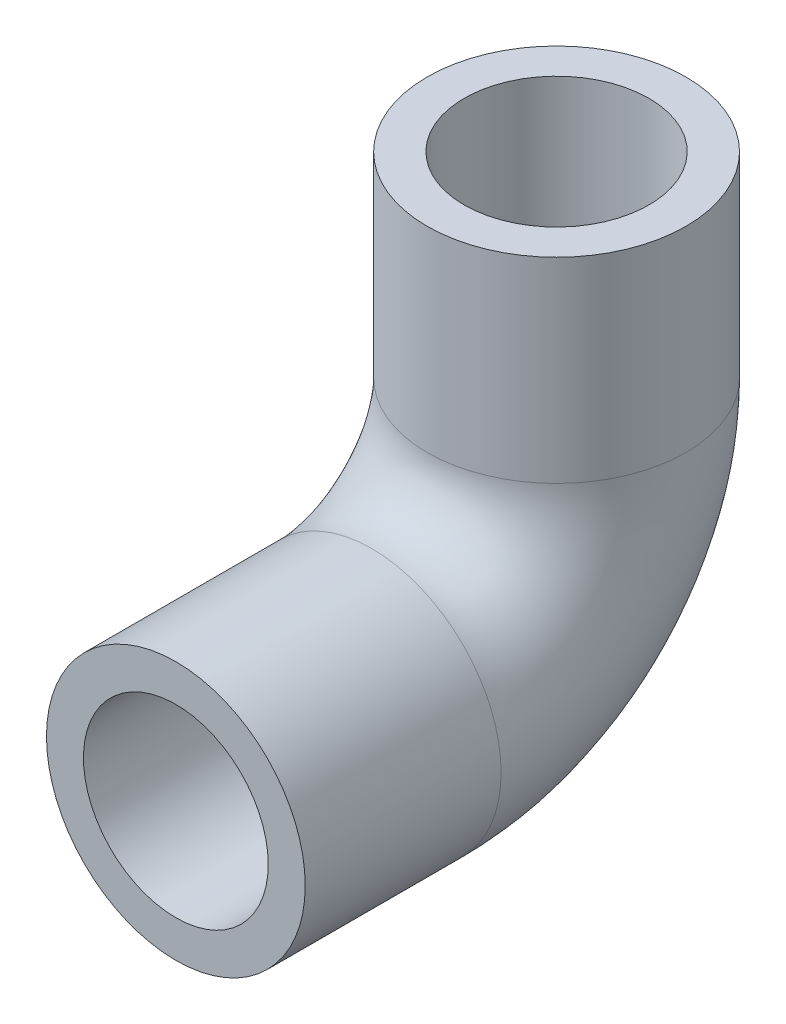
SolidWorks part; units mm, degrees
ref_plane "Front" through (0, 0, 0) normal (0, 0, 1) x (1, 0, 0)
ref_plane "Top" through (0, 0, 0) normal (0, 1, 0) x (1, 0, 0)
ref_plane "Right" through (0, 0, 0) normal (1, 0, 0) x (0, 0, -1)
sketch "Sketch1" plane through (0, 0, 0) normal (0, 1, 0) x (1, 0, 0)
  circle A0 centre (0, 0) radius 6.35
  circle A1 centre (0, 0) radius 8.89
extrude "Boss-Extrude1" add sketch "Sketch1" along normal blind 13.462
sketch "Sketch2" plane through (0, 0, 0) normal (1, 0, 0) x (0, 0, -1)
  line L0 (0, 0) -> (-12.7, 0) construction
  line L1 (-12.7, 0) -> (-12.7, -12.7) construction
  arc A0 (0, 0) -> (-12.7, -12.7) centre (-12.7, 0) cw
sketch "Sketch3" plane through (0, 0, 0) normal (0, -1, 0) x (1, 0, 0)
  circle A0 centre (0, 0) radius 6.35
  circle A1 centre (0, 0) radius 8.89
sweep "Sweep1" add profiles "Sketch3" path "Sketch2"
sketch "Sketch5" plane through (0, 0, 12.7) normal (0, 0, 1) x (1, 0, 0)
  circle A0 centre (0, -12.7) radius 6.3493
  circle A1 centre (0, -12.7) radius 8.89
extrude "Boss-Extrude2" add sketch "Sketch5" along normal blind 13.462
